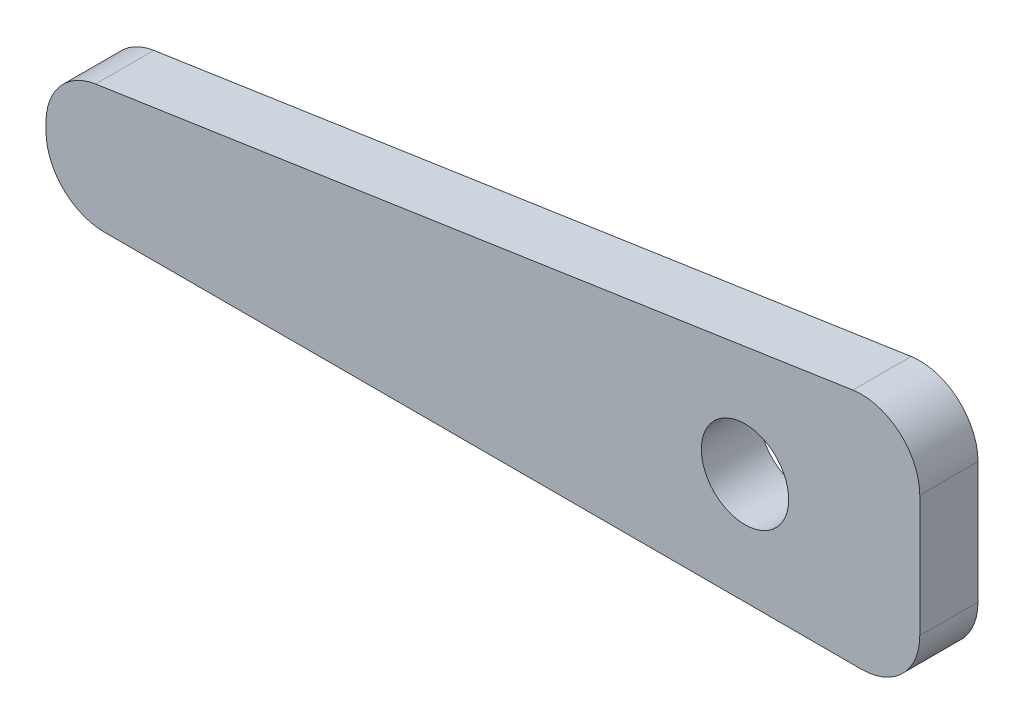
SolidWorks part; units mm, degrees
ref_plane "Front Plane" through (0, 0, 0) normal (0, 0, 1) x (1, 0, 0)
ref_plane "Top Plane" through (0, 0, 0) normal (0, 1, 0) x (1, 0, 0)
ref_plane "Right Plane" through (0, 0, 0) normal (1, 0, 0) x (0, 0, -1)
sketch "Sketch1" plane through (0, 0, 0) normal (0, 0, 1) x (1, 0, 0)
  line L2 (-381, 3.175) -> (-381, 3.6157)
  line L3 (-378.296, 6.7556) -> (-337.021, 12.9469)
  line L12 (-342.9, 0) -> (-342.9, 12.065)
  line L13 (-333.375, 9.807) -> (-333.375, 3.175)
  line L15 (-336.55, 0) -> (-377.825, 0)
  circle A0 centre (-342.9, 6.0325) radius 2.3813
  arc A1 (-381, 3.6157) -> (-378.296, 6.7556) centre (-377.825, 3.6157) cw
  arc A2 (-377.825, 0) -> (-381, 3.175) centre (-377.825, 3.175) cw
  arc A3 (-333.375, 3.175) -> (-336.55, 0) centre (-336.55, 3.175) cw
  arc A4 (-333.375, 9.807) -> (-337.021, 12.9469) centre (-336.55, 9.807) ccw
  point P3 (-381, 6.35)
  point P10 (-381, 0)
  dimension "D8" = 4.7625
  dimension "D2" = 3.175
  dimension "D1" = 6.35
  dimension "D7" = 9.525
extrude "Boss-Extrude1" add sketch "Sketch1" along normal blind 3.175 contours A2 L15 L12 A0 L3 A1 L2 | L13 A4 L3 L12 A0 L15 A3
